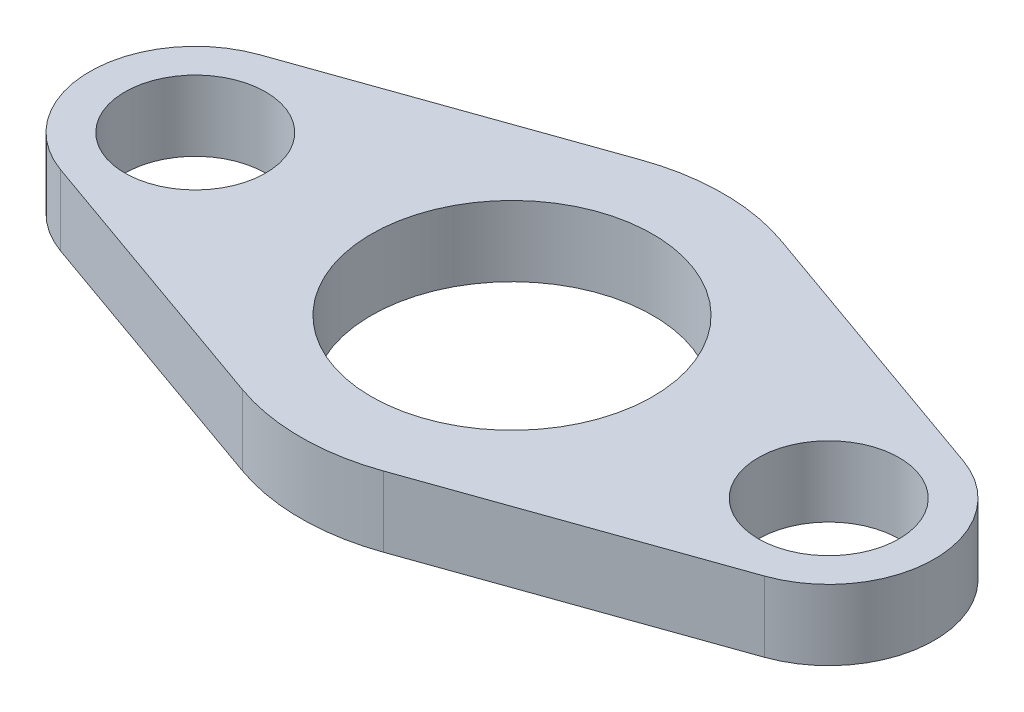
SolidWorks part; units mm, degrees
ref_plane "Front Plane" through (0, 0, 0) normal (0, 0, 1) x (1, 0, 0)
ref_plane "Top Plane" through (0, 0, 0) normal (0, 1, 0) x (1, 0, 0)
ref_plane "Right Plane" through (0, 0, 0) normal (1, 0, 0) x (0, 0, -1)
sketch "Sketch1" plane through (0, 0, 0) normal (0, 1, 0) x (1, 0, 0)
  line L0 (0, 0) -> (-14059.3261, 0) construction
  line L1 (0, 0) -> (0, 14059.3261) construction
  line L2 (10, 28.2843) -> (50, 14.1421)
  line L3 (-10, 28.2843) -> (-50, 14.1421)
  line L4 (-50, -14.1421) -> (-10, -28.2843)
  line L5 (10, -28.2843) -> (50, -14.1421)
  circle A0 centre (0, 0) radius 20
  circle A1 centre (45, 0) radius 10
  arc A2 (-10, -28.2843) -> (10, -28.2843) centre (0, 0) ccw
  arc A3 (50, -14.1421) -> (50, 14.1421) centre (45, 0) ccw
  arc A4 (-50, -14.1421) -> (-50, 14.1421) centre (-45, 0) cw
  circle A5 centre (-45, 0) radius 10
  arc A6 (10, 28.2843) -> (-10, 28.2843) centre (0, 0) ccw
  point P9 (0, 0)
  dimension "D1" = 40
  dimension "D2" = 60
  dimension "D3" = 20
  dimension "D4" = 30
extrude "Boss-Extrude1" add sketch "Sketch1" along normal blind 10
